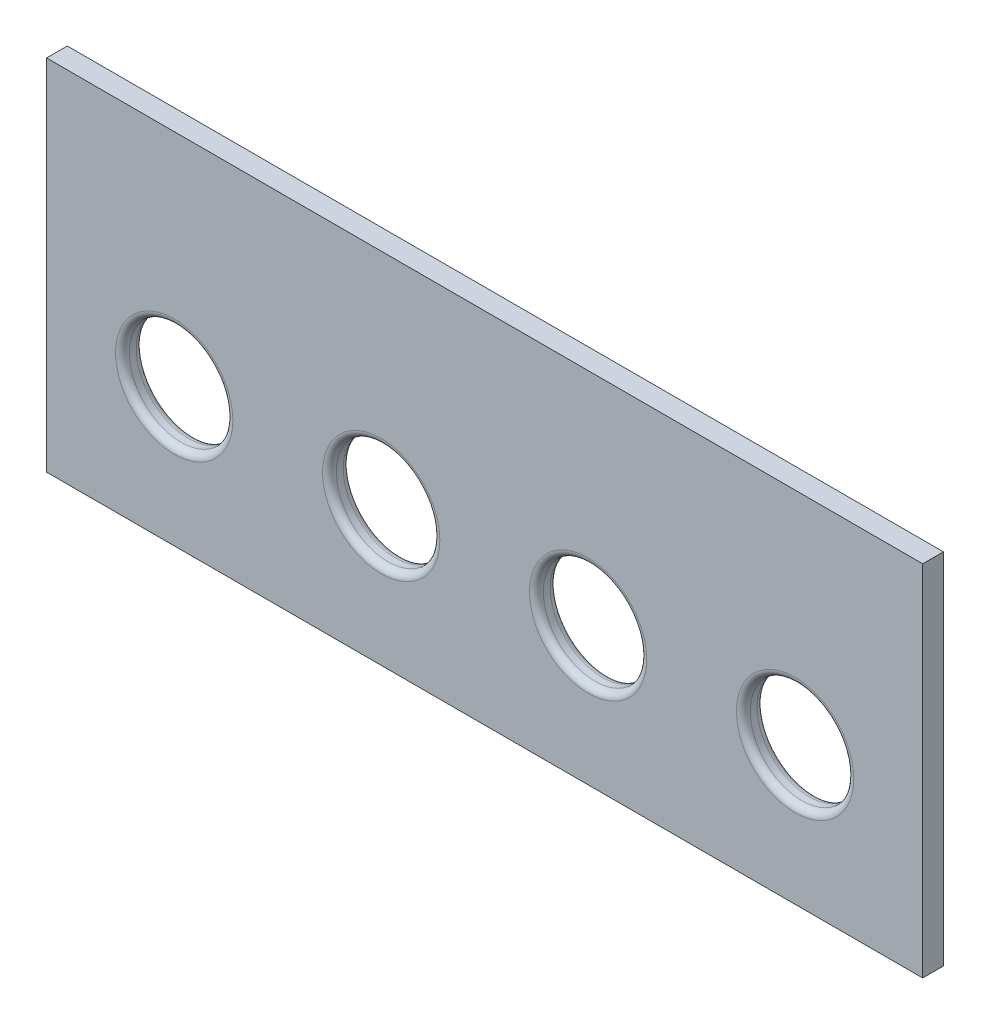
SolidWorks part; units mm, degrees
ref_plane "前视基准面" through (0, 0, 0) normal (0, 0, 1) x (1, 0, 0)
ref_plane "上视基准面" through (0, 0, 0) normal (0, 1, 0) x (1, 0, 0)
ref_plane "右视基准面" through (0, 0, 0) normal (1, 0, 0) x (0, 0, -1)
sketch "草图1" plane through (0, 0, 0) normal (0, 0, 1) x (1, 0, 0)
  line L1 (0, 0) -> (127, 0)
  line L2 (0, 0) -> (0, -52)
  line L3 (0, -52) -> (127, -52)
  line L4 (127, 0) -> (127, -52)
extrude "凸台-拉伸1" add sketch "草图1" along normal blind 3
sketch "草图2" plane through (0, 0, 3) normal (0, 0, 1) x (1, 0, 0)
  circle A0 centre (78.5, -32) radius 7.5
  circle A1 centre (108.5, -32) radius 7.5
  circle A2 centre (48.5, -32) radius 7.5
  circle A3 centre (18.5, -32) radius 7.5
extrude "切除-拉伸1" cut sketch "草图2" against normal blind 3
fillet "圆角1" radius 1 8 edges at (116, -32, 0) (116, -32, 3) (86, -32, 0) (86, -32, 3) (56, -32, 0) (56, -32, 3) (26, -32, 0) (26, -32, 3)
